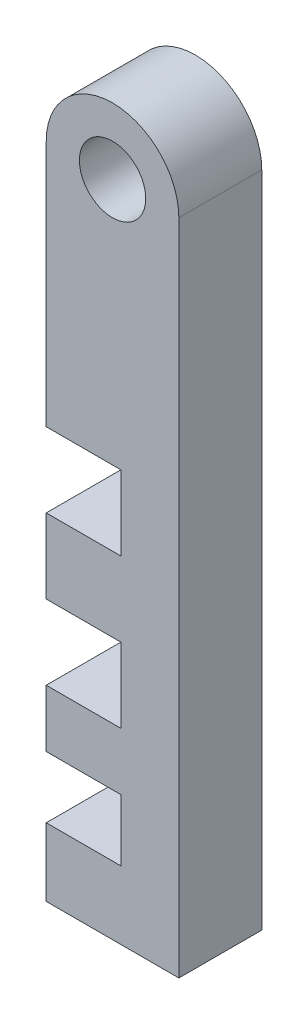
SolidWorks part; units mm, degrees
ref_plane "Plan de face" through (0, 0, 0) normal (0, 0, 1) x (1, 0, 0)
ref_plane "Plan de dessus" through (0, 0, 0) normal (0, 1, 0) x (1, 0, 0)
ref_plane "Plan de droite" through (0, 0, 0) normal (1, 0, 0) x (0, 0, -1)
sketch "Esquisse1" plane through (0, 0, 0) normal (0, 0, 1) x (1, 0, 0)
  line L0 (-60.8186, 1.0046) -> (-60.8186, 11.3062)
  line L1 (-60.8186, -3.6092) -> (-60.8186, 1.0046)
  line L2 (-56.3186, -3.6092) -> (-60.8186, -3.6092)
  line L3 (-56.3186, -8.1092) -> (-56.3186, -3.6092)
  line L4 (-60.8186, -8.1092) -> (-56.3186, -8.1092)
  line L5 (-60.8186, -12.6092) -> (-60.8186, -8.1092)
  line L6 (-56.3186, -12.6092) -> (-60.8186, -12.6092)
  line L7 (-56.3186, -17.1092) -> (-56.3186, -12.6092)
  line L8 (-60.8186, -17.1092) -> (-56.3186, -17.1092)
  line L9 (-60.8186, -20.5733) -> (-60.8186, -17.1092)
  line L10 (-56.3186, -20.5733) -> (-60.8186, -20.5733)
  line L11 (-56.3186, -20.5733) -> (-56.3186, -24.2941)
  line L12 (-60.8186, -24.2941) -> (-56.3186, -24.2941)
  line L13 (-60.8186, -28.4024) -> (-60.8186, -24.2941)
  line L14 (-52.8186, -28.4024) -> (-60.8186, -28.4024)
  line L15 (-52.8186, 11.3062) -> (-52.8186, -28.4024)
  arc A0 (-52.8186, 11.3062) -> (-60.8186, 11.3062) centre (-56.8186, 11.3062) ccw
  circle A1 centre (-56.8186, 11.3062) radius 2
extrude "Boss.-Extru.1" add sketch "Esquisse1" along normal blind 5
